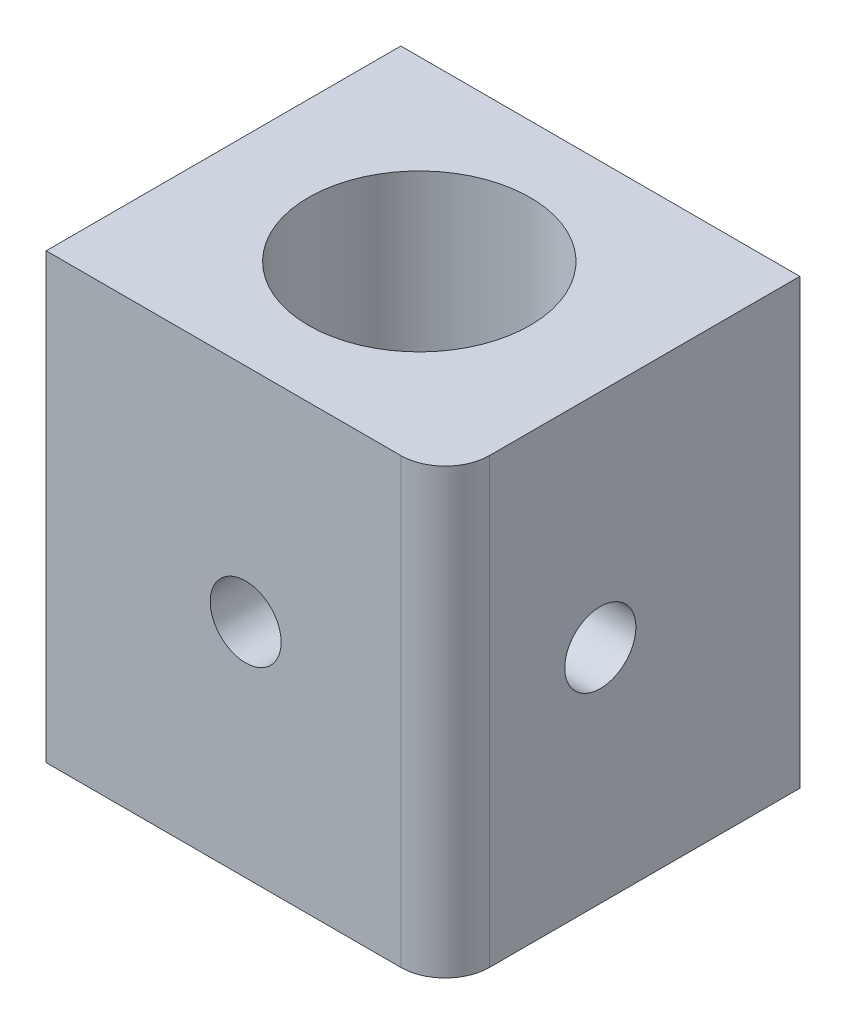
SolidWorks part; units mm, degrees
ref_plane "Front Plane" through (0, 0, 0) normal (0, 0, 1) x (1, 0, 0)
ref_plane "Top Plane" through (0, 0, 0) normal (0, 1, 0) x (1, 0, 0)
ref_plane "Right Plane" through (0, 0, 0) normal (1, 0, 0) x (0, 0, -1)
sketch "Sketch1" plane through (0, 0, 0) normal (0, 1, 0) x (1, 0, 0)
  line L1 (-24.0371, 11.234) -> (-6.0371, 11.234)
  line L2 (-24.0371, 11.234) -> (-24.0371, -4.766)
  line L3 (-24.0371, -4.766) -> (-6.0371, -4.766)
  line L4 (-6.0371, 11.234) -> (-6.0371, -4.766)
  circle A0 centre (-15.2043, 3.234) radius 5
  dimension "D1" = 10
  dimension "D3" = 8
  dimension "D2" = 16
  dimension "D4" = 18
extrude "Boss-Extrude2" add sketch "Sketch1" along normal blind 20
sketch "Sketch3" plane through (-6.0371, 0, 0) normal (1, 0, 0) x (0, 0, -1)
  line L0 (11.234, 20) -> (11.234, 0) construction
  line L1 (-4.766, 0) -> (11.234, 0) construction
  circle A0 centre (2.234, 10) radius 1.605
  dimension "D1" = 3.21
  dimension "D2" = 9
  dimension "D3" = 10
extrude "Cut-Extrude1" cut sketch "Sketch3" against normal blind 10
sketch "Sketch4" plane through (0, 0, 4.766) normal (0, 0, 1) x (1, 0, 0)
  line L0 (-24.0371, 20) -> (-6.0371, 20) construction
  line L1 (-6.0371, 20) -> (-6.0371, 0) construction
  circle A0 centre (-15.0371, 10) radius 1.6
  dimension "D1" = 3.2
  dimension "D2" = 10
  dimension "D3" = 9
extrude "Cut-Extrude2" cut sketch "Sketch4" against normal blind 10
fillet "Fillet1" radius 2 1 edges at (-6.0371, 10, 4.766)
